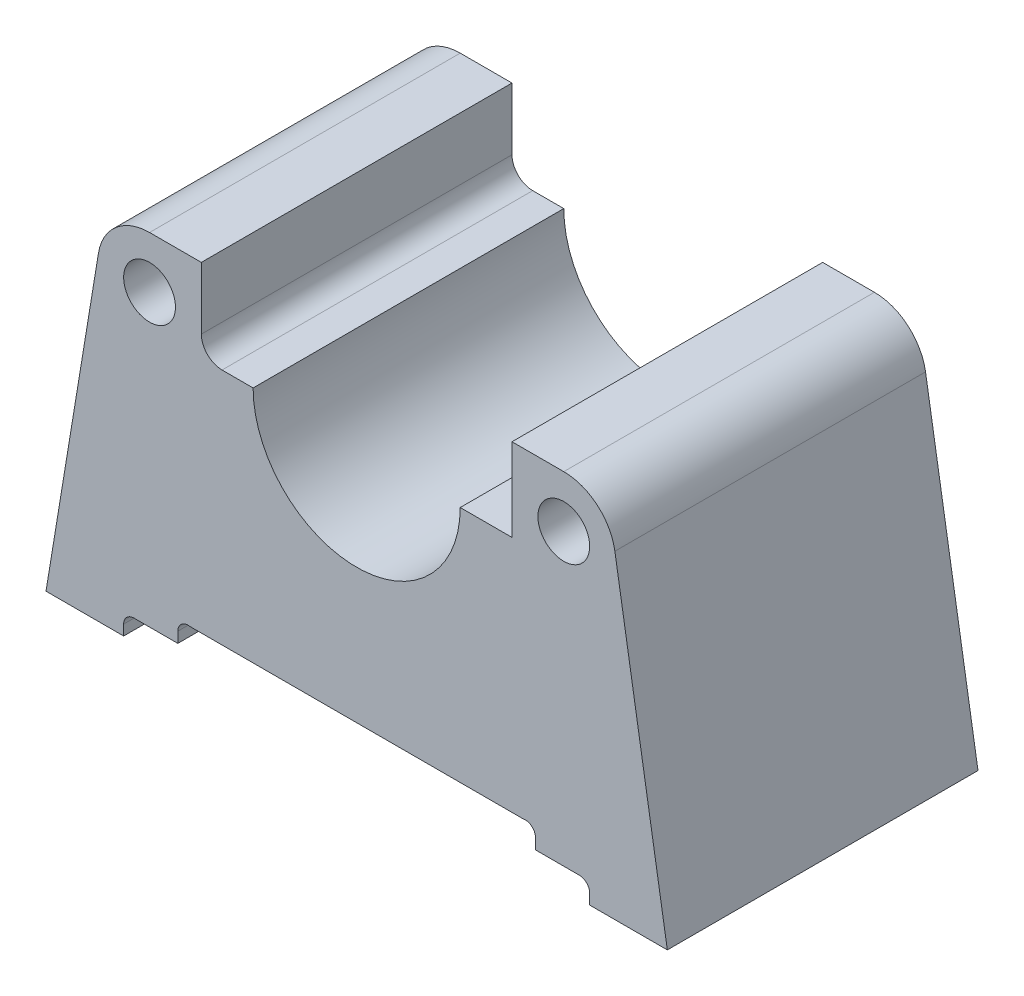
SolidWorks part; units mm, degrees
ref_plane "Front Plane" through (0, 0, 0) normal (0, 0, 1) x (1, 0, 0)
ref_plane "Top Plane" through (0, 0, 0) normal (0, 1, 0) x (1, 0, 0)
ref_plane "Right Plane" through (0, 0, 0) normal (1, 0, 0) x (0, 0, -1)
sketch "Sketch1" plane through (0, 0, 0) normal (0, 0, 1) x (1, 0, 0)
  line L0 (0, 0) -> (0, -50000) construction
  line L1 (0, 0) -> (-50000, 0) construction
  line L3 (17.2717, 3.0225) -> (17.2717, 2)
  line L4 (17.2717, 2) -> (21.5, 2)
  line L5 (22.5, 1) -> (22.5, 0)
  line L6 (22.5, 0) -> (30, 0)
  line L7 (30, 0) -> (24.9337, 30.8112)
  line L8 (20, 35) -> (15, 35)
  line L10 (-30, 0) -> (-24.9337, 30.8112)
  line L11 (-22.5, 0) -> (-30, 0)
  line L12 (-22.5, 1) -> (-22.5, 0)
  line L13 (-17.2717, 2) -> (-21.5, 2)
  line L14 (-17.2717, 3.0225) -> (-17.2717, 2)
  line L16 (-15, 35) -> (-15, 29)
  line L17 (-13, 27) -> (-10, 27)
  line L19 (15, 35) -> (20, 35)
  line L20 (13, 27) -> (10, 27)
  line L21 (-15, 35) -> (-20, 35)
  line L22 (15, 35) -> (15, 29)
  line L24 (17.2717, 3.0225) -> (17.2717, 2)
  line L25 (17.2717, 2) -> (22.5, 2)
  line L26 (15, 35) -> (20, 35)
  line L27 (15, 27) -> (10, 27)
  line L28 (15, 35) -> (15, 27)
  line L29 (-16.0609, 4) -> (16.0609, 4)
  arc A0 (24.9337, 30.8112) -> (20, 35) centre (20, 30) ccw
  arc A1 (-24.9337, 30.8112) -> (-20, 35) centre (-20, 30) cw
  arc A3 (-10, 27) -> (10, 27) centre (0, 27) ccw
  circle A4 centre (-20, 30) radius 2.5
  circle A5 centre (20, 30) radius 2.5
  arc A6 (24.9337, 30.8112) -> (20, 35) centre (20, 30) ccw
  arc A7 (21.5, 2) -> (22.5, 1) centre (21.5, 1) cw
  arc A8 (16.0609, 4) -> (17.2717, 3.0225) centre (16.2717, 3.0225) cw
  arc A9 (-17.2717, 3.0225) -> (-16.0609, 4) centre (-16.2717, 3.0225) cw
  arc A10 (-22.5, 1) -> (-21.5, 2) centre (-21.5, 1) cw
  arc A11 (13, 27) -> (15, 29) centre (13, 29) ccw
  arc A12 (-15, 29) -> (-13, 27) centre (-13, 29) ccw
  point P2 (0, 0)
  point P13 (0, 35)
  point P21 (24.245, 35)
  point P24 (-24.245, 35)
  point P43 (-17.2717, 4)
  point P46 (-22.5, 2)
  point P50 (-15, 27)
  point P51 (0, 0)
  point P52 (16.0609, 3.0225)
  point P53 (0, 0)
  dimension "D6" = 5
  dimension "D7" = 30
  dimension "D9" = 10
  dimension "D11" = 5
  dimension "D13" = 1
  dimension "D14" = 2
  dimension "D2" = 45
  dimension "D3" = 60
  dimension "D4" = 2
  dimension "D5" = 4
  dimension "D8" = 35
  dimension "D10" = 40
  dimension "D12" = 27
extrude "Boss-Extrude1" add sketch "Sketch1" along normal mid plane 30
